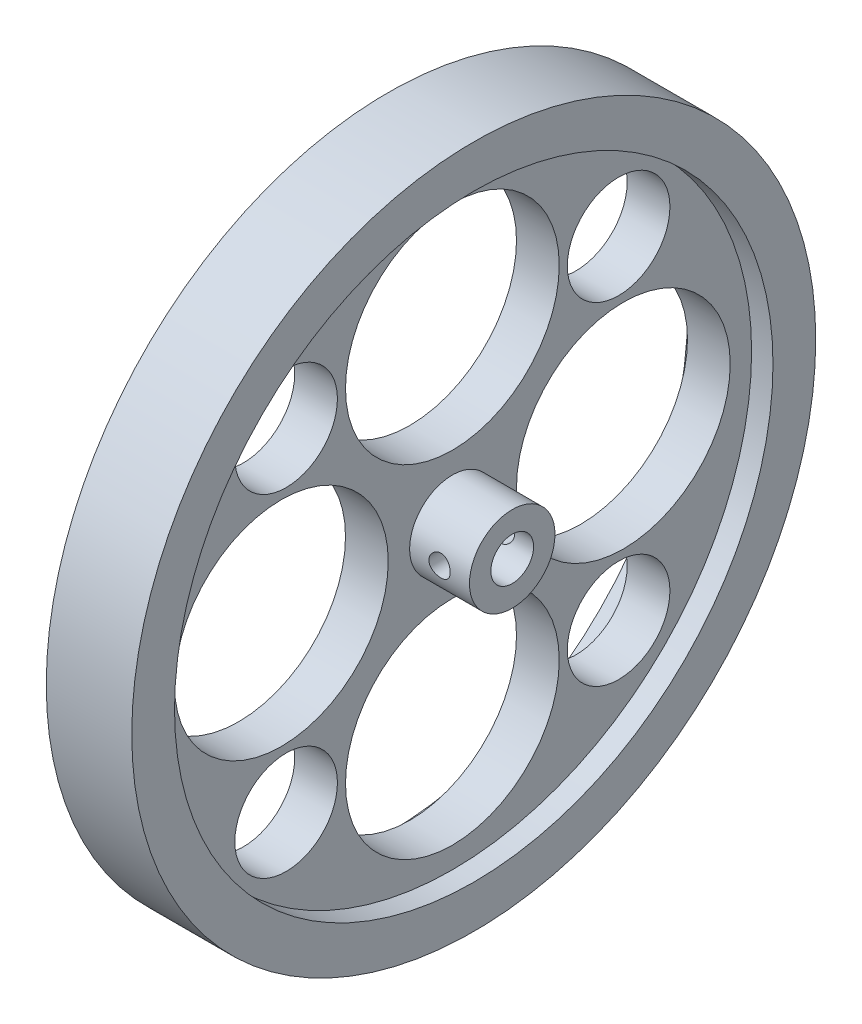
SolidWorks part; units mm, degrees
ref_plane "Front Plane" through (0, 0, 0) normal (0, 0, 1) x (1, 0, 0)
ref_plane "Top Plane" through (0, 0, 0) normal (0, 1, 0) x (1, 0, 0)
ref_plane "Right Plane" through (0, 0, 0) normal (1, 0, 0) x (0, 0, -1)
sketch "Sketch1" plane through (0, 0, 0) normal (1, 0, 0) x (0, 0, -1)
  circle A0 centre (0, 0) radius 2.5
  circle A1 centre (0, 0) radius 5
  dimension "D1" = 5
  dimension "D2" = 10
extrude "Boss-Extrude1" add sketch "Sketch1" along normal mid plane 14.5
sketch "Sketch4" plane through (0, 0, 0) normal (0, 0, 1) x (1, 0, 0)
  line L0 (-4.75, 5) -> (-4.75, 35)
  line L1 (7.25, 5) -> (-7.25, 5) construction
  line L2 (-4.75, 35) -> (-7.25, 35)
  line L3 (-7.25, 35) -> (-7.25, 40)
  line L4 (-7.25, 40) -> (2.75, 40)
  line L5 (2.75, 40) -> (2.75, 35)
  line L6 (2.75, 35) -> (0.25, 35)
  line L7 (0.25, 35) -> (0.25, 5)
  line L8 (-7.25, 5) -> (-7.25, -5) construction
  line L9 (0, 0) -> (-17.3071, 0) construction
  line L10 (-4.75, 5) -> (0.25, 5)
  line L11 (-4.75, 5) -> (0.25, 5)
  dimension "D1" = 10
  dimension "D2" = 2.5
  dimension "D3" = 0
  dimension "D4" = 2.5
  dimension "D5" = 40
  dimension "D6" = 35
revolve "Revolve4" add sketch "Sketch4" angle 360 about L9
sketch "Sketch5" plane through (0.25, 0, 0) normal (1, 0, 0) x (0, 0, -1)
  line L0 (0, 0) -> (-19.4454, 19.4454) construction
  line L1 (0, 0) -> (0, 40) construction
  circle A0 centre (0, 0) radius 27.5 construction
  circle A1 centre (0, 0) radius 20 construction
  circle A2 centre (0, 20) radius 12.5
  circle A3 centre (-19.4454, 19.4454) radius 6
  circle A4 centre (0, 0) radius 40 construction
  circle A5 centre (0, 0) radius 5 construction
  dimension "D1" = 25
  dimension "D2" = 12
  dimension "D4" = 55
  dimension "D3" = 45
extrude "Cut-Extrude1" cut sketch "Sketch5" against normal through all both and the other way through all
pattern_circular "CirPattern1" count 4 every 90 about axis through (0, 0, 0) along (1, 0, 0) of "Cut-Extrude1"
sketch "Sketch6" plane through (0, 0, 0) normal (0, 0, 1) x (1, 0, 0)
  line L0 (7.25, -5) -> (7.25, 5) construction
  circle A0 centre (3.75, 0) radius 1.25
  dimension "D1" = 3.5
  dimension "D2" = 2.5
extrude "Cut-Extrude2" cut sketch "Sketch6" against normal mid plane 20
